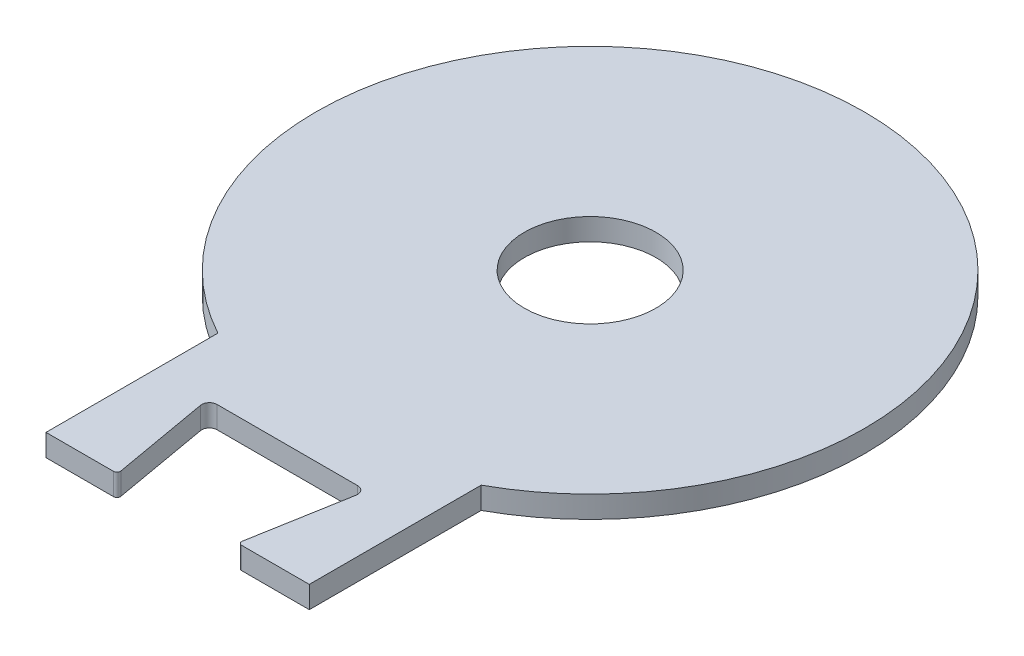
SolidWorks part; units mm, degrees
ref_plane "Front Plane" through (0, 0, 0) normal (0, 0, 1) x (1, 0, 0)
ref_plane "Top Plane" through (0, 0, 0) normal (0, 1, 0) x (1, 0, 0)
ref_plane "Right Plane" through (0, 0, 0) normal (1, 0, 0) x (0, 0, -1)
sketch "Sketch1" plane through (0, 0, 0) normal (0, 1, 0) x (1, 0, 0)
  line L0 (-6, 6) -> (-6, -13.2915)
  line L1 (-6, -19) -> (-2.7023, -19)
  line L2 (6, -19) -> (6, -13.2915)
  line L3 (6, 6) -> (-6, 6)
  line L4 (-6, -13.2915) -> (-6, -19)
  line L5 (6, -13.2915) -> (6, 6)
  line L6 (0, -19) -> (0, 0) construction
  line L7 (-2.6007, -19) -> (-3.5, -13.9) construction
  line L8 (-3.5, -13.9) -> (0, -13.9) construction
  line L9 (-2.7023, -19) -> (-3.6192, -13.8)
  line L10 (-3.6192, -13.8) -> (0, -13.8)
  line L11 (-2.6992, -19.0174) -> (-3.6192, -13.8) construction
  line L12 (2.7023, -19) -> (6, -19)
  line L13 (3.6192, -13.8) -> (0, -13.8)
  line L14 (2.7023, -19) -> (3.6192, -13.8)
  circle A0 centre (0, 0) radius 3
  dimension "D1" = 6
  dimension "D5" = 6
  dimension "D7" = 80
  dimension "D2" = 25
  dimension "D3" = 6
  dimension "D4" = 12
  dimension "D8" = 3.5
  dimension "D9" = 5.1
  dimension "D10" = 0.1
extrude "Boss-Extrude1" add sketch "Sketch1" along normal blind 1
sketch "Sketch2" plane through (0, 0, 0) normal (0, 1, 0) x (1, 0, 0)
  circle A0 centre (0, 0) radius 12.5
  circle A1 centre (0, 0) radius 3
  dimension "D1" = 25
extrude "Boss-Extrude2" add sketch "Sketch2" along normal blind 1
sketch "Sketch3" plane through (0, 0, 0) normal (0, -1, 0) x (1, 0, 0)
  line L0 (-3, 0) -> (-3, 4)
  line L1 (3, 0) -> (3, 4)
  arc A0 (-3, 0) -> (3, 0) centre (0, 0) ccw
  arc A1 (-3, 4) -> (3, 4) centre (0, 0) ccw
extrude "Boss-Extrude3" [suppressed] add sketch "Sketch3" along normal blind 4
fillet "Fillet1" [suppressed] radius 0.5
fillet "Fillet2" [suppressed] radius 1
sketch "Sketch4" plane through (0, 1, 0) normal (0, 1, 0) x (1, 0, 0)
  line L0 (-6, -10.9659) -> (-6, -19) construction
  line L1 (-6, -18.8) -> (6, -18.8)
  line L2 (-6, -18.8) -> (-6, -19)
  line L3 (-6, -19) -> (6, -19)
  line L4 (6, -18.8) -> (6, -19)
  dimension "D1" = 0.2
extrude "Cut-Extrude1" cut sketch "Sketch4" against normal blind 4
fillet "Fillet3" radius 0.35 2 edges at (3.6192, 0.5, 13.8) (-3.6192, 0.5, 13.8)
fillet "Fillet4" radius 0.15 2 edges at (2.7375, 0.5, 18.8) (-2.7375, 0.5, 18.8)
